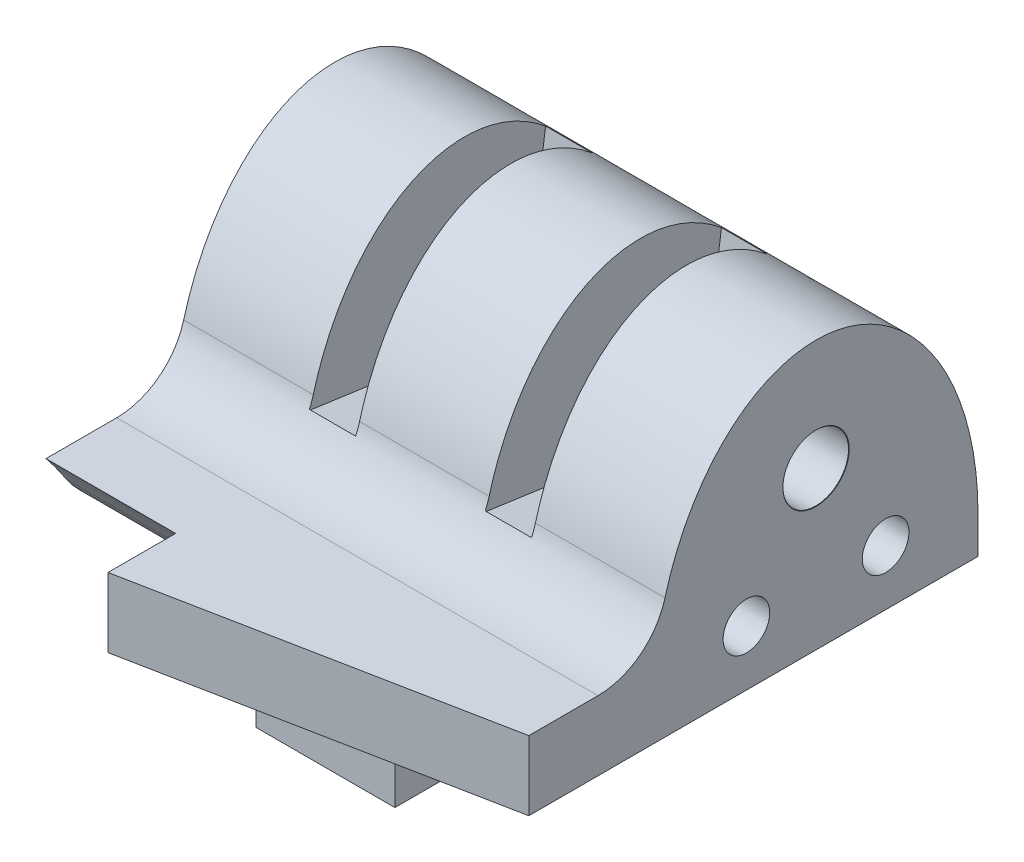
SolidWorks part; units mm, degrees
material "ABS"
ref_plane "Front Plane" through (0, 0, 0) normal (1, 0, 0) x (0, 1, 0)
ref_plane "Top Plane" through (0, 0, 0) normal (0, 0, 1) x (0, 1, 0)
ref_plane "Right Plane" through (0, 0, 0) normal (0, 1, 0) x (-1, 0, 0)
ref_plane "Plane1" through (8.89, 0, 0) normal (1, 0, 0) x (0, 1, 0)
sketch "Sketch1" plane through (0, 0, 0) normal (1, 0, 0) x (0, 1, 0)
  line L0 (0, 0) -> (0, 35.56)
  line L1 (0, 0) -> (-4.6261, 0) construction
  line L2 (0, 0) -> (2.54, 0)
  line L3 (0, 35.56) -> (4.7625, 35.56)
  line L4 (4.7625, 35.56) -> (4.7625, 26.0701)
  line L5 (2.54, 11.1125) -> (18.415, 11.1125) construction
  arc A0 (4.7625, 26.0701) -> (8.2778, 21.4738) centre (9.525, 26.0701) ccw
  ellipse E0 centre (2.54, 11.1125) end of major axis (-13.335, 11.1125) minor radius 11.1125 (2.54, 0) -> (8.2778, 21.4738) ccw
  point P12 (10.795, 11.1125)
  dimension "D3" = 22.225
  dimension "D4" = 4.7625
  dimension "D1" = 2.54
  dimension "D2" = 35.56
  dimension "D5" = 4.7625
  dimension "D6" = 31.75
  dimension "D7" = 7.62
extrude "Boss-Extrude1" add sketch "Sketch1" along normal blind 33.02
hole_wizard "M4 Clearance Hole1" positions "Sketch2" profile "Sketch3" hole size "M4" standard "ANSI Metric" end condition through all
sketch "Sketch2" plane through (33.02, 0, 0) normal (1, 0, 0) x (0, 0, -1)
  point P0 (-11.1125, 10.795)
sketch "Sketch3" plane through (33.02, 10.795, 11.1125) normal (0, 1, 0) x (0, 0, -1)
  line L0 (0, 0) -> (0, 33.02)
  line L1 (0, 33.02) -> (2.25, 33.02)
  line L2 (2.25, 33.02) -> (2.25, 0.021)
  line L3 (2.25, 0.021) -> (2.275, 0)
  line L5 (2.275, 0) -> (0, 0)
  line L6 (-2.25, 0.021) -> (-2.275, 0) construction
  line L11 (0, -6.35) -> (0, 107.95) construction
  dimension "Thru Hole Dia." = 4.5
  dimension "Thru Hole Depth" = 33.02
  dimension "Near C'Sink Dia." = 4.55
  dimension "Near C'Sink Angle" = 100
sketch "Sketch5" plane through (8.89, 0, 0) normal (-1, 0, 0) x (0, -1, 0)
  line L0 (0, 0) -> (0, 35.56) construction
  line L1 (0, 25.4) -> (9.525, 25.4)
  line L2 (0, 25.4) -> (0, 0)
  line L3 (0, 0) -> (9.525, 0)
  line L4 (9.525, 25.4) -> (9.525, 0)
  line L5 (4.7625, 19.05) -> (4.7625, 6.35)
  dimension "D1" = 12.7
  dimension "D2" = 4.7625
  dimension "D3" = 9.525
  dimension "D4" = 6.35
  dimension "D5" = 25.4
extrude "Boss-Extrude2" add sketch "Sketch5" against normal blind 9.525
hole_wizard "#8 Clearance Hole1" positions "Sketch6" profile "Sketch7" hole size "#8" standard "ANSI Inch" end condition through all
sketch "Sketch6" plane through (0, 0, 0) normal (-1, 0, 0) x (0, 0, 1)
  point P0 (6.35, -4.7625)
  point P3 (19.05, -4.7625)
sketch "Sketch7" plane through (0, -4.7625, 6.35) normal (0, 1, 0) x (0, 0, 1)
  line L0 (0, 0) -> (0, 33.02)
  line L1 (0, 33.02) -> (2.2479, 33.02)
  line L2 (2.2479, 33.02) -> (2.2479, 0)
  line L5 (2.2479, 0) -> (0, 0)
  line L11 (0, -6.35) -> (0, 107.95) construction
  dimension "Thru Hole Dia." = 4.4958
  dimension "Thru Hole Depth" = 33.02
sketch "Sketch8" plane through (0, 4.7625, 0) normal (0, 1, 0) x (-1, 0, 0)
  line L0 (-33.02, 35.56) -> (-8.89, 35.56)
  line L1 (-8.89, 12.6726) -> (-8.89, -12.6726) construction
  line L2 (-33.02, 35.56) -> (0, 35.56) construction
  line L3 (-8.89, 35.56) -> (-33.02, 30.815)
  line L4 (-33.02, 26.0701) -> (-33.02, 35.56) construction
  line L5 (-33.02, 30.815) -> (-33.02, 35.56)
extrude "Cut-Extrude1" cut sketch "Sketch8" against normal through all both and the other way through all
sketch "Sketch9" plane through (8.89, 0, 0) normal (1, 0, 0) x (0, 1, 0)
  line L0 (7.4702, 21.6755) -> (5.416, 7.0592)
  line L1 (5.416, 7.0592) -> (16.2696, 5.5338)
  line L2 (5.416, 7.0592) -> (14.9798, 7.0592) construction
  line L5 (6.0788, 11.7753) -> (10.795, 11.1125) construction
  line L6 (10.1322, 6.3963) -> (10.795, 11.1125) construction
  line L7 (-9.525, 0) -> (93.5503, 0) construction
  line L8 (5.416, 7.0592) -> (49.4335, 0.8729) construction
  arc A0 (7.4702, 21.6755) -> (16.2696, 5.5338) centre (13.9484, 14.7377) cw
  ellipse E0 centre (2.54, 11.1125) end of major axis (-13.335, 11.1125) minor radius 11.1125 (2.54, 0) -> (8.2778, 21.4738) ccw construction
  dimension "D1" = 8
  dimension "D2" = 4.7625
  dimension "D3" = 4.7625
  dimension "D4" = 44.45
extrude "Cut-Extrude3" cut sketch "Sketch9" along normal blind 3.175
pattern_linear "LPattern1" count 2 spacing 12.065 along (1, 0, 0) of "Cut-Extrude3"
ref_plane "Plane3" through (27.94, 0, 0) normal (1, 0, 0) x (0, 0, -1)
sketch "Sketch12" plane through (27.94, 0, 0) normal (1, 0, 0) x (0, 0, -1)
  line L0 (0, 0) -> (-35.56, 0) construction
  line L1 (-3.5941, 0) -> (-9.0805, 0)
  line L2 (-3.5941, 0) -> (-3.5941, 3.81)
  line L3 (-3.5941, 3.81) -> (-9.0805, 3.81)
  line L4 (-9.0805, 0) -> (-9.0805, 3.81)
  line L5 (-11.1125, 2.54) -> (-11.1125, 18.415) construction
  line L6 (-18.6309, 0) -> (-13.1445, 0)
  line L7 (-18.6309, 0) -> (-18.6309, 3.81)
  line L8 (-18.6309, 3.81) -> (-13.1445, 3.81)
  line L9 (-13.1445, 0) -> (-13.1445, 3.81)
  line L10 (-15.8877, 6.9776) -> (-18.6309, 5.3938)
  line L11 (-18.6309, 5.3938) -> (-18.6309, 2.2262)
  line L12 (-18.6309, 2.2262) -> (-15.8877, 0.6424)
  line L13 (-15.8877, 0.6424) -> (-13.1445, 2.2262)
  line L14 (-13.1445, 2.2262) -> (-13.1445, 5.3938)
  line L15 (-13.1445, 5.3938) -> (-15.8877, 6.9776)
  line L16 (-6.3373, 6.9776) -> (-9.0805, 5.3938)
  line L17 (-9.0805, 5.3938) -> (-9.0805, 2.2262)
  line L18 (-9.0805, 2.2262) -> (-6.3373, 0.6424)
  line L19 (-6.3373, 0.6424) -> (-3.5941, 2.2262)
  line L20 (-3.5941, 2.2262) -> (-3.5941, 5.3938)
  line L21 (-3.5941, 5.3938) -> (-6.3373, 6.9776)
  circle A0 centre (-15.8877, 3.81) radius 2.7432 construction
  circle A1 centre (-6.3373, 3.81) radius 2.7432 construction
  dimension "D1" = 5.4864
  dimension "D2" = 5.4864
  dimension "D3" = 3.81
  dimension "D4" = 3.81
  dimension "D5" = 2.032
  dimension "D6" = 2.032
extrude "Cut-Extrude4" cut sketch "Sketch12" against normal blind 2.413 contours L13 L12 L7 L6 L9 | L14 L15 L10 L11 L8 | L20 L21 L16 L17 L3 | L18 L19 L2 L3 L4 | L19 L18 L4 L1 L2 | L12 L13 L9 L8 L7
sketch "Sketch13" plane through (33.02, 0, 0) normal (1, 0, 0) x (0, 1, 0)
  line L0 (3.81, 18.6309) -> (3.81, 13.1445) construction
  circle A0 centre (3.81, 15.8877) radius 1.6
  circle A1 centre (3.81, 6.3373) radius 1.6
  dimension "D1" = 3.2
extrude "Cut-Extrude5" cut sketch "Sketch13" against normal blind 9.525
sketch "Sketch15" plane through (0, 4.7625, 0) normal (1, 0, 0) x (0, 1, 0)
  line L5 (-4.7625, 0) -> (-4.7625, 27.94)
  line L6 (-4.7625, 0) -> (-4.7625, 35.56) construction
  line L7 (-4.7625, 27.94) -> (-14.2875, 27.94)
  line L8 (-14.2875, 27.94) -> (-14.2875, 0)
  line L9 (-14.2875, 0) -> (-4.7625, 0)
  circle A0 centre (-14.9225, 49.4762) radius 23.8125
  arc A1 (-1.8883, 29.5478) -> (-4.7625, 24.2335) centre (1.5875, 24.2335) ccw
  line M12 (-4.7625, 0) -> (-4.7625, 35.56)
  line M13 (-4.7625, 35.56) -> (0, 35.56)
  line M14 (0, 35.56) -> (0, 26.0701)
  dimension "D2" = 47.625
  dimension "D4" = 6.35
  dimension "D1" = 27.94
  dimension "D3" = 10.16
extrude "Cut-Extrude6" cut sketch "Sketch15" along normal blind 8.89 and the other way through all contours A0 L7 L8 M14 M13 M12 | A0 M12 M13 M14 | A0 A1 L5 | L8 A0 L5 L9 M12 | A0 L8 L7
equation "\"D1@Sketch13\"=3.2mm"
